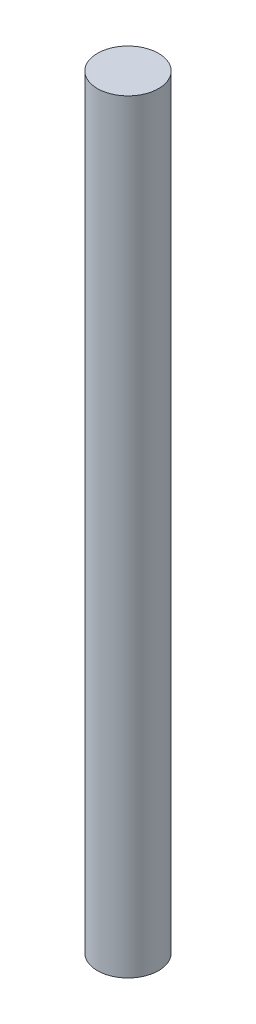
SolidWorks part; units mm, degrees
ref_plane "Front Plane" through (0, 0, 0) normal (0, 0, 1) x (1, 0, 0)
ref_plane "Top Plane" through (0, 0, 0) normal (0, 1, 0) x (1, 0, 0)
ref_plane "Right Plane" through (0, 0, 0) normal (1, 0, 0) x (0, 0, -1)
sketch "Sketch1" plane through (0, 0, 0) normal (0, 1, 0) x (1, 0, 0)
  circle A0 centre (0, 0) radius 8
  dimension "D1" = 16
extrude "Boss-Extrude1" add sketch "Sketch1" along normal blind 200
